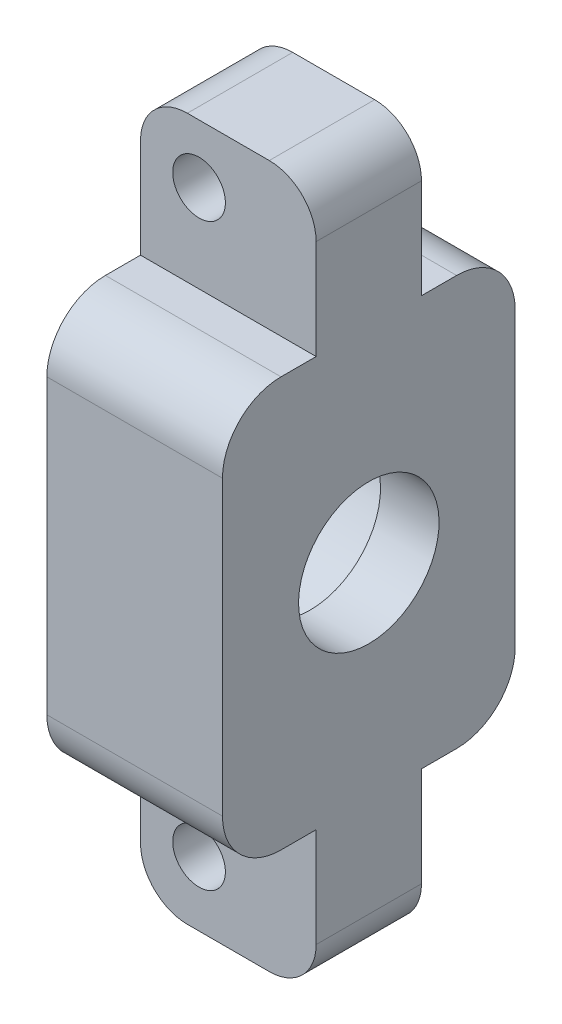
SolidWorks part; units mm, degrees
ref_plane "Front Plane" through (0, 0, 0) normal (0, 0, 1) x (1, 0, 0)
ref_plane "Top Plane" through (0, 0, 0) normal (0, 1, 0) x (1, 0, 0)
ref_plane "Right Plane" through (0, 0, 0) normal (1, 0, 0) x (0, 0, -1)
sketch "Sketch2" plane through (0, 0, 0) normal (0, 0, 1) x (1, 0, 0)
  line L1 (-7.5, 30) -> (7.5, 30)
  line L2 (-7.5, 30) -> (-7.5, -30)
  line L3 (-7.5, -30) -> (7.5, -30)
  line L4 (7.5, 30) -> (7.5, -30)
  line L5 (-7.5, 30) -> (7.5, -30) construction
  line L6 (-7.5, -30) -> (7.5, 30) construction
  point P0 (0, 0)
  dimension "D1" = 60
  dimension "D2" = 15
extrude "Boss-Extrude1" add sketch "Sketch2" along normal mid plane 25
sketch "Sketch3" plane through (7.5, 0, 0) normal (1, 0, 0) x (0, 0, -1)
  line L0 (-12.5, 30) -> (12.5, 30) construction
  line L2 (-4.5, 30) -> (-4.5, 17.5)
  line L4 (4.5, 30) -> (4.5, 17.5)
  line L9 (55, 0) -> (-55, 0) construction
  line L10 (-12.5, 30) -> (-4.5, 30)
  line L11 (-12.5, 30) -> (-12.5, 17.5)
  line L12 (-12.5, 17.5) -> (-4.5, 17.5)
  line L13 (-4.5, 30) -> (-4.5, 17.5)
  line L14 (12.5, 30) -> (4.5, 30)
  line L15 (12.5, 30) -> (12.5, 17.5)
  line L16 (12.5, 17.5) -> (4.5, 17.5)
  line L17 (4.5, 30) -> (4.5, 17.5)
  line L18 (4.5, -30) -> (4.5, -17.5)
  line L19 (12.5, -17.5) -> (4.5, -17.5)
  line L20 (12.5, -30) -> (12.5, -17.5)
  line L21 (12.5, -30) -> (4.5, -30)
  line L22 (-4.5, -30) -> (-4.5, -17.5)
  line L23 (-12.5, -17.5) -> (-4.5, -17.5)
  line L24 (-12.5, -30) -> (-12.5, -17.5)
  line L25 (-12.5, -30) -> (-4.5, -30)
  line L26 (4.5, -30) -> (4.5, -17.5)
  line L27 (-4.5, -30) -> (-4.5, -17.5)
  line M4 (12.5, -30) -> (12.5, 30)
  line M5 (12.5, 30) -> (-12.5, 30)
  line M6 (-12.5, 30) -> (-12.5, -30)
  line M7 (-12.5, -30) -> (12.5, -30)
  dimension "D1" = 9
extrude "Cut-Extrude1" cut sketch "Sketch3" against normal through all contours L23 L22 M6 M7 | L19 L18 M4 M7 | L16 L4 M4 M5 | L12 L2 M6 M5
sketch "Sketch4" plane through (0, 0, 4.5) normal (0, 0, 1) x (1, 0, 0)
  line L0 (-7.5, -30) -> (7.5, -30) construction
  line L1 (-7.5, 30) -> (-7.5, 17.5) construction
  line L2 (-7.5, -30) -> (-7.5, -17.5) construction
  circle A0 centre (-2.5, 25) radius 2.25
  circle A1 centre (-2.5, -24.5) radius 2.25
  dimension "D1" = 4.5
  dimension "D2" = 4.5
  dimension "D3" = 49.5
  dimension "D4" = 5.5
  dimension "D5" = 5
  dimension "D6" = 5
extrude "Cut-Extrude2" cut sketch "Sketch4" against normal through all
fillet "Fillet1" radius 5 4 edges at (0, -17.5, 12.5) (0, -17.5, -12.5) (0, 17.5, -12.5) (0, 17.5, 12.5)
fillet "Fillet2" radius 4 4 edges at (7.5, -30, 0) (-7.5, -30, 0) (-7.5, 30, 0) (7.5, 30, 0)
sketch "Sketch5" plane through (-7.5, 0, 0) normal (-1, 0, 0) x (0, 0, 1)
  circle A0 centre (0, 0) radius 6
  dimension "D1" = 12
extrude "Cut-Extrude3" cut sketch "Sketch5" against normal through all
sketch "Sketch6" plane through (-7.5, 0, 0) normal (-1, 0, 0) x (0, 0, 1)
  circle A0 centre (0, 0) radius 10
  dimension "D1" = 20
extrude "Cut-Extrude4" cut sketch "Sketch6" against normal blind 10
